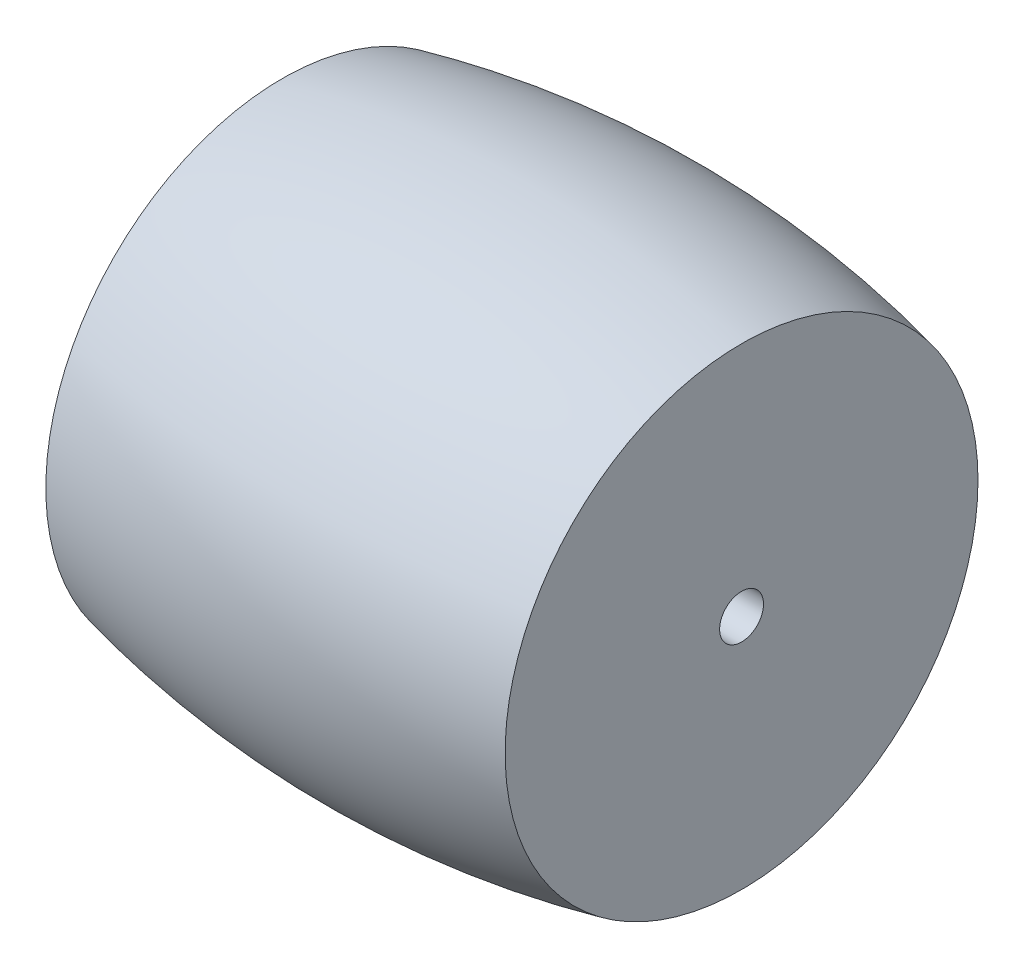
SolidWorks part; units mm, degrees
material "PET"
ref_plane "Front Plane" through (0, 0, 0) normal (0, 0, 1) x (1, 0, 0)
ref_plane "Top Plane" through (0, 0, 0) normal (0, 1, 0) x (1, 0, 0)
ref_plane "Right Plane" through (0, 0, 0) normal (1, 0, 0) x (0, 0, -1)
sketch "Sketch2" plane through (0, 0, 0) normal (0, 0, 1) x (1, 0, 0)
  line L0 (14.6474, 0) -> (14.6474, 15.0813) construction
  line L1 (14.6474, 0) -> (14.6474, 15.0813)
  line L2 (23.6421, 0) -> (-23.6421, 0) construction
  line L3 (23.6421, 0) -> (-23.6421, 0)
  line L4 (-14.6474, 0) -> (-14.6474, 15.0813) construction
  line L5 (-14.6474, 0) -> (-14.6474, 15.0813)
  circle A0 centre (0, -49.0934) radius 65.825 construction
  circle A1 centre (0, -49.0934) radius 65.825
sketch "Sketch3" plane through (0, 0, 0) normal (0, 0, 1) x (1, 0, 0)
  line L0 (23.6421, 0) -> (-23.6421, 0) construction
  line L1 (23.6421, 0) -> (-23.6421, 0) construction
  line L2 (-14.6474, 0) -> (-14.6474, 15.0813) construction
  line L3 (-14.6474, 1.4) -> (-14.6474, 15.0813)
  line L4 (14.6474, 0) -> (14.6474, 15.0813) construction
  line L5 (14.6474, 1.4) -> (14.6474, 15.0813)
  line L6 (-14.6474, 1.4) -> (14.6474, 1.4)
  line L7 (-11.6474, 15.6929) -> (-11.6474, 3.4)
  line L8 (-11.6474, 3.4) -> (-1.5, 3.4)
  line L9 (-1.5, 3.4) -> (-1.5, 16.7145)
  line L10 (1.5, 16.7145) -> (1.5, 3.4)
  line L11 (1.5, 3.4) -> (11.6474, 3.4)
  line L12 (11.6474, 3.4) -> (11.6474, 15.6929)
  line L13 (0, 16.7316) -> (0, 1.4) construction
  line L14 (-11.6474, 3.4) -> (-14.6474, 3.4) construction
  line L15 (11.6474, 3.4) -> (14.6474, 3.4) construction
  circle A0 centre (0, -49.0934) radius 65.825 construction
  arc A1 (14.6474, 15.0813) -> (11.6474, 15.6929) centre (0, -49.0934) ccw
  arc A2 (-11.6474, 15.6929) -> (-14.6474, 15.0813) centre (0, -49.0934) ccw
  arc A3 (1.5, 16.7145) -> (-1.5, 16.7145) centre (0, -49.0934) ccw
  point P21 (0, 14.1849)
  point P23 (0, 16.7316)
  point P24 (-14.6474, 1.7259)
  dimension "D1" = 1.4
  dimension "D2" = 3
  dimension "D3" = 3
  dimension "D4" = 2
revolve "Revolve1" add sketch "Sketch3" angle 360 about L1
sketch "Sketch4" plane through (0, 0, 0) normal (0, 0, 1) x (1, 0, 0)
  line L0 (-14.6474, 0) -> (-14.6474, 15.0813) construction
  line L1 (-14.6474, 12.0813) -> (-14.6474, 15.0813)
  line L2 (14.6474, 0) -> (14.6474, 15.0813) construction
  line L3 (14.6474, 12.0813) -> (14.6474, 15.0813)
  circle A0 centre (0, -49.0934) radius 65.825 construction
  arc A1 (14.6474, 15.0813) -> (-14.6474, 15.0813) centre (0, -49.0934) ccw
  arc A2 (14.6474, 12.0813) -> (-14.6474, 12.0813) centre (0, -52.0934) ccw
  dimension "D1" = 3
revolve "Revolve2" add sketch "Sketch4" angle 360 about L3
